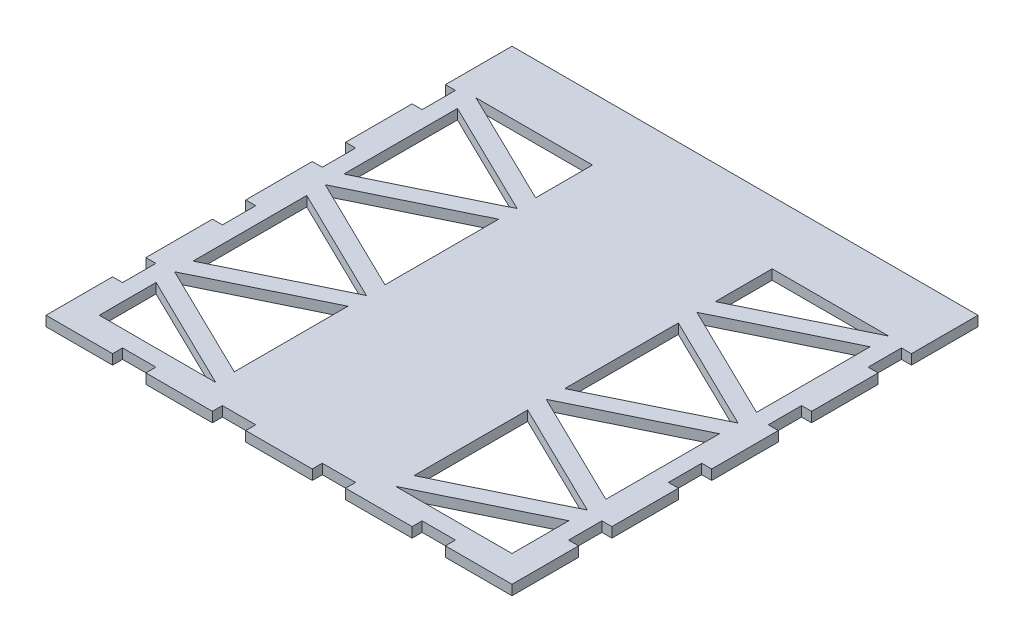
SolidWorks part; units mm, degrees
ref_plane "Front Plane" through (0, 0, 0) normal (0, 0, 1) x (1, 0, 0)
ref_plane "Top Plane" through (0, 0, 0) normal (0, 1, 0) x (1, 0, 0)
ref_plane "Right Plane" through (0, 0, 0) normal (1, 0, 0) x (0, 0, -1)
sketch "Sketch1" plane through (0, 0, 0) normal (0, 1, 0) x (1, 0, 0)
  line L1 (70, 70) -> (-70, 70)
  line L2 (70, 70) -> (70, -70)
  line L3 (70, -70) -> (-70, -70)
  line L4 (-70, 70) -> (-70, -70)
  line L5 (70, 70) -> (-70, -70) construction
  line L6 (70, -70) -> (-70, 70) construction
  point P0 (0, 0)
  dimension "D1" = 140
  dimension "D2" = 140
extrude "Boss-Extrude1" add sketch "Sketch1" along normal blind 3
sketch "Sketch2" plane through (0, 3, 0) normal (0, 1, 0) x (1, 0, 0)
  line L0 (62, -62) -> (27, -62)
  line L1 (27, -62) -> (62, -44.9294)
  line L2 (62, -44.9294) -> (62, -62)
  line L3 (70, -70) -> (70, 70) construction
  line L4 (-70, -70) -> (70, -70) construction
  line L5 (27, -56.437) -> (62, -39.3663)
  line L6 (62, -39.3663) -> (27, -22.2957)
  line L7 (27, -22.2957) -> (27, -56.437)
  line L10 (27, -16.7327) -> (62, 0.3379)
  line L11 (62, -33.8033) -> (62, 0.3379)
  line L12 (27, -16.7327) -> (62, -33.8033)
  line L14 (62, 5.901) -> (27, -11.1697)
  line L15 (27, 22.9716) -> (62, 5.901)
  line L16 (27, -11.1697) -> (27, 22.9716)
  line L18 (27, 28.5346) -> (62, 45.6052)
  line L19 (62, 45.6052) -> (62, 11.464)
  line L20 (27, 28.5346) -> (62, 11.464)
  line L22 (27, 34.0976) -> (62, 51.1683)
  line L23 (27, 51.1683) -> (27, 34.0976)
  line L25 (62, 51.1683) -> (27, 51.1683)
  line L26 (0, 70) -> (0, -70) construction
  line L27 (-27, -62) -> (-62, -44.9294)
  line L28 (-62, -62) -> (-27, -62)
  line L29 (-62, -44.9294) -> (-62, -62)
  line L30 (-62, -39.3663) -> (-27, -22.2957)
  line L31 (-27, -56.437) -> (-62, -39.3663)
  line L32 (-27, -22.2957) -> (-27, -56.437)
  line L33 (-27, -16.7327) -> (-62, -33.8033)
  line L34 (-62, -33.8033) -> (-62, 0.3379)
  line L35 (-27, -16.7327) -> (-62, 0.3379)
  line L36 (-27, 22.9716) -> (-62, 5.901)
  line L37 (-27, -11.1697) -> (-27, 22.9716)
  line L38 (-62, 5.901) -> (-27, -11.1697)
  line L39 (-27, 28.5346) -> (-62, 11.464)
  line L40 (-62, 45.6052) -> (-62, 11.464)
  line L41 (-27, 28.5346) -> (-62, 45.6052)
  line L42 (-62, 51.1683) -> (-27, 51.1683)
  line L43 (-27, 34.0976) -> (-62, 51.1683)
  line L44 (-27, 51.1683) -> (-27, 34.0976)
  point P30 (0, 0)
  dimension "D1" = 8
  dimension "D2" = 8
  dimension "D3" = 35
  dimension "D4" = 26
  dimension "D5" = 26
  dimension "D6" = 5
extrude "Cut-Extrude1" cut sketch "Sketch2" against normal blind 10
sketch "Sketch3" plane through (0, 3, 0) normal (0, 1, 0) x (1, 0, 0)
  line L0 (70, -70) -> (70, 70) construction
  line L1 (70, -50) -> (67, -50)
  line L2 (70, -50) -> (70, -40)
  line L3 (70, -40) -> (67, -40)
  line L4 (67, -50) -> (67, -40)
  line L5 (-70, -70) -> (70, -70) construction
  line L22 (0, -70) -> (0, 70) construction
  line L23 (70, 70) -> (-70, 70) construction
  line L43 (70, -20) -> (70, -10)
  line L44 (70, -20) -> (67, -20)
  line L45 (67, -20) -> (67, -10)
  line L46 (70, -10) -> (67, -10)
  line L47 (70, 10) -> (70, 20)
  line L48 (70, 10) -> (67, 10)
  line L49 (67, 10) -> (67, 20)
  line L50 (70, 20) -> (67, 20)
  line L51 (70, 40) -> (70, 50)
  line L52 (70, 40) -> (67, 40)
  line L53 (67, 40) -> (67, 50)
  line L54 (70, 50) -> (67, 50)
  line L55 (-70, -40) -> (-67, -40)
  line L56 (-67, -50) -> (-67, -40)
  line L57 (-70, -50) -> (-67, -50)
  line L58 (-70, -50) -> (-70, -40)
  line L59 (-70, -20) -> (-67, -20)
  line L60 (-67, -20) -> (-67, -10)
  line L61 (-70, -10) -> (-67, -10)
  line L62 (-70, -20) -> (-70, -10)
  line L63 (-70, 10) -> (-67, 10)
  line L64 (-67, 10) -> (-67, 20)
  line L65 (-70, 20) -> (-67, 20)
  line L66 (-70, 10) -> (-70, 20)
  line L67 (-70, 40) -> (-67, 40)
  line L68 (-67, 40) -> (-67, 50)
  line L69 (-70, 50) -> (-67, 50)
  line L70 (-70, 40) -> (-70, 50)
  dimension "D1" = 3
  dimension "D2" = 10
  dimension "D3" = 20
  dimension "D4" = 4
extrude "Cut-Extrude2" cut sketch "Sketch3" against normal blind 13
sketch "Sketch4" plane through (0, 3, 0) normal (0, 1, 0) x (1, 0, 0)
  line L0 (-70, -70) -> (70, -70) construction
  line L1 (-50, -70) -> (-40, -70)
  line L2 (-50, -70) -> (-50, -67)
  line L3 (-50, -67) -> (-40, -67)
  line L4 (-40, -70) -> (-40, -67)
  line L5 (-70, -50) -> (-70, -70) construction
  line L6 (-20, -70) -> (-20, -67)
  line L7 (-20, -70) -> (-10, -70)
  line L8 (-10, -70) -> (-10, -67)
  line L9 (-20, -67) -> (-10, -67)
  line L10 (10, -70) -> (10, -67)
  line L11 (10, -70) -> (20, -70)
  line L12 (20, -70) -> (20, -67)
  line L13 (10, -67) -> (20, -67)
  line L14 (40, -70) -> (40, -67)
  line L15 (40, -70) -> (50, -70)
  line L16 (50, -70) -> (50, -67)
  line L17 (40, -67) -> (50, -67)
  point P6 (-45, -70)
  dimension "D1" = 3
  dimension "D2" = 20
  dimension "D3" = 10
  dimension "D4" = 4
extrude "Cut-Extrude3" cut sketch "Sketch4" against normal blind 13
